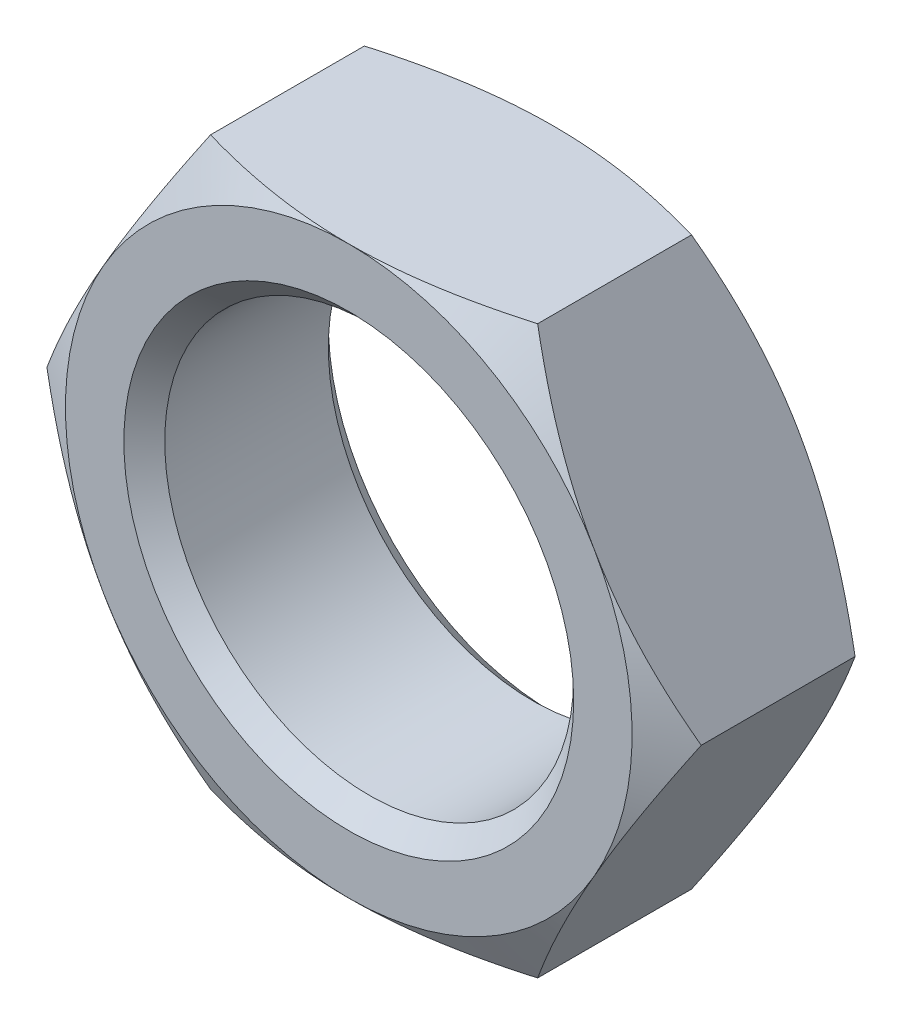
SolidWorks part; units mm, degrees
ref_plane "Płaszczyzna przednia" through (0, 0, 0) normal (0, 0, 1) x (1, 0, 0)
ref_plane "Płaszczyzna górna" through (0, 0, 0) normal (0, 1, 0) x (1, 0, 0)
ref_plane "Płaszczyzna prawa" through (0, 0, 0) normal (1, 0, 0) x (0, 0, -1)
sketch "Szkic1" plane through (0, 0, 0) normal (0, 0, 1) x (1, 0, 0)
  line L1 (-4, 6.9282) -> (-8, 0)
  line L2 (-8, 0) -> (-4, -6.9282)
  line L3 (-4, -6.9282) -> (4, -6.9282)
  line L4 (4, -6.9282) -> (8, 0)
  line L5 (8, 0) -> (4, 6.9282)
  line L6 (4, 6.9282) -> (-4, 6.9282)
  circle A0 centre (0, 0) radius 6.9282 construction
  dimension "D1" = 16
extrude "Dodanie-wyciągnięcie1" add sketch "Szkic1" along normal blind 5
sketch "Szkic2" plane through (0, 0, 5) normal (0, 0, 1) x (1, 0, 0)
  circle A0 centre (0, 0) radius 5
  dimension "D1" = 10
extrude "Wytnij-wyciągnięcie1" cut sketch "Szkic2" against normal blind 5
chamfer "Sfazowanie1" distance 0.5 angle 45 2 edges at (5, 0, 0) (5, 0, 5)
ref_plane "Płaszczyzna1" through (4, 6.9282, 0) normal (-1, 0, 0) x (0, 0, 1)
sketch "Szkic6" plane through (0, 0, 0) normal (0, 0, -1) x (-1, 0, 0)
  line L0 (-4, 6.9282) -> (4, 6.9282) construction
  circle A0 centre (0, 0) radius 6.9282
extrude "Wytnij-wyciągnięcie2" cut sketch "Szkic6" against normal blind 10 draft 60 flip side to cut
sketch "Szkic7" plane through (0, 0, 5) normal (0, 0, 1) x (1, 0, 0)
  line L1 (4, 6.9282) -> (-4, 6.9282) construction
  circle A0 centre (0, 0) radius 6.9282
extrude "Wytnij-wyciągnięcie3" cut sketch "Szkic7" against normal blind 10 draft 60 flip side to cut
